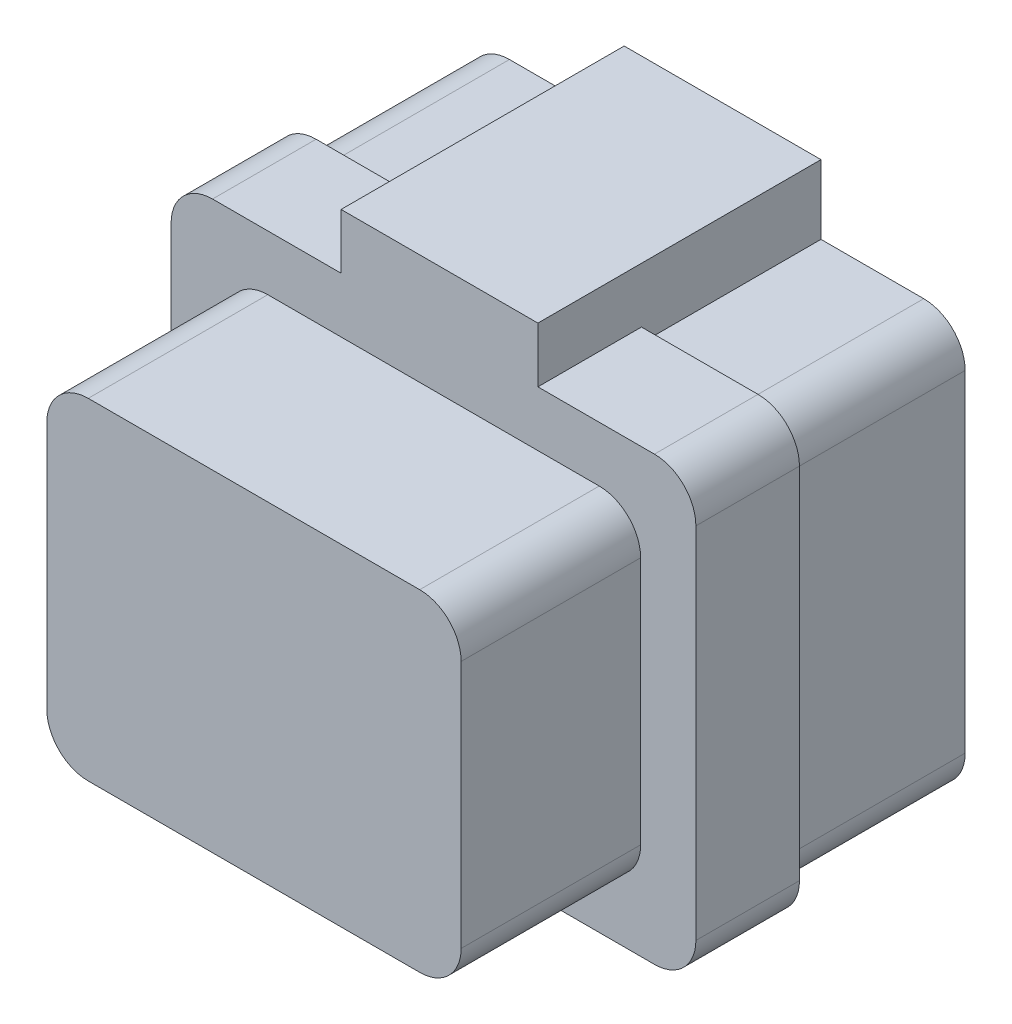
SolidWorks part; units mm, degrees
ref_plane "正面" through (0, 0, 0) normal (0, 0, 1) x (1, 0, 0)
ref_plane "平面" through (0, 0, 0) normal (0, 1, 0) x (1, 0, 0)
ref_plane "右側面" through (0, 0, 0) normal (1, 0, 0) x (0, 0, -1)
sketch "ｽｹｯﾁ1" plane through (0, 0, 0) normal (0, 0, 1) x (1, 0, 0)
  line L1 (0, 0) -> (38, 0)
  line L2 (0, 0) -> (0, 32)
  line L3 (0, 32) -> (38, 32)
  line L4 (38, 0) -> (38, 32)
  dimension "D1" = 38
  dimension "D2" = 32
extrude "ﾎﾞｽ - 押し出し1" add sketch "ｽｹｯﾁ1" along normal blind 7.5
sketch "ｽｹｯﾁ2" plane through (0, 0, 7.5) normal (0, 0, 1) x (1, 0, 0)
  line L8 (4, 28) -> (4, 4)
  line L9 (4, 4) -> (34, 4)
  line L10 (34, 4) -> (34, 28)
  line L11 (34, 28) -> (4, 28)
  line L12 (4, 28) -> (4, 4)
  line L13 (4, 4) -> (34, 4)
  line L14 (34, 4) -> (34, 28)
  line L15 (34, 28) -> (4, 28)
  dimension "D1" = 4
extrude "ﾎﾞｽ - 押し出し2" add sketch "ｽｹｯﾁ2" along normal blind 13
sketch "ｽｹｯﾁ3" plane through (0, 0, 0) normal (0, 0, -1) x (-1, 0, 0)
  line L12 (-1, 1) -> (-1, 31)
  line L13 (-1, 31) -> (-37, 31)
  line L14 (-37, 31) -> (-37, 1)
  line L15 (-37, 1) -> (-1, 1)
  line L16 (-1, 1) -> (-1, 31)
  line L17 (-1, 31) -> (-37, 31)
  line L18 (-37, 31) -> (-37, 1)
  line L19 (-37, 1) -> (-1, 1)
  dimension "D1" = 1
extrude "ﾎﾞｽ - 押し出し3" add sketch "ｽｹｯﾁ3" along normal blind 13
fillet "ﾌｨﾚｯﾄ1" radius 3 12 edges at (34, 4, 14) (4, 4, 14) (4, 28, 14) (34, 28, 14) (37, 1, -6.5) (38, 0, 3.75) (0, 0, 3.75) (1, 1, -6.5) (0, 32, 3.75) (1, 31, -6.5) (37, 31, -6.5) (38, 32, 3.75)
sketch "ｽｹｯﾁ4" plane through (0, 31, 0) normal (0, 1, 0) x (1, 0, 0)
  line L0 (4, 13) -> (34, 13) construction
  line L1 (12.3078, 13) -> (26.5597, 13)
  line L2 (12.3078, 13) -> (12.3078, -7.5)
  line L3 (12.3078, -7.5) -> (26.5597, -7.5)
  line L4 (26.5597, 13) -> (26.5597, -7.5)
  line L5 (31, -7.5) -> (7, -7.5) construction
extrude "ﾎﾞｽ - 押し出し4" add sketch "ｽｹｯﾁ4" along normal blind 5
sketch "ｽｹｯﾁ5" plane through (0, 0, -13) normal (0, 0, -1) x (-1, 0, 0)
  circle A4 centre (-19.4338, 18.5) radius 10.9106
extrude "ｶｯﾄ - 押し出し1" cut sketch "ｽｹｯﾁ5" against normal blind 1
